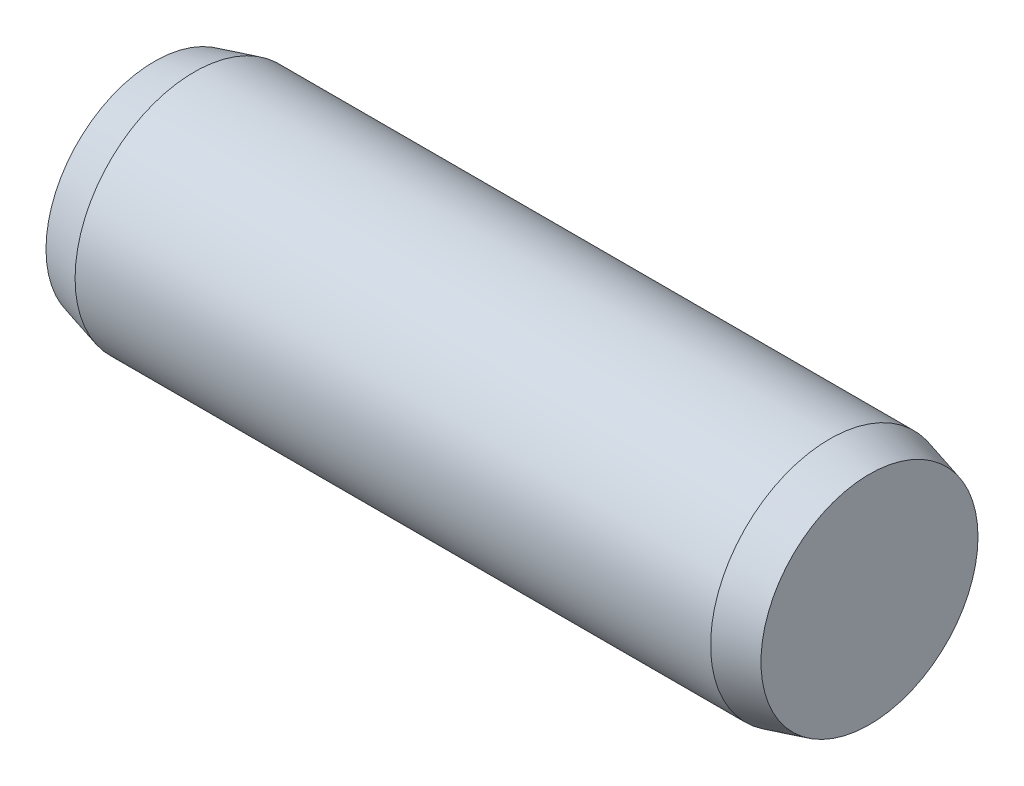
SolidWorks part; units mm, degrees
ref_plane "Front Plane" through (0, 0, 0) normal (0, 0, 1) x (1, 0, 0)
ref_plane "Top Plane" through (0, 0, 0) normal (0, 1, 0) x (1, 0, 0)
ref_plane "Right Plane" through (0, 0, 0) normal (1, 0, 0) x (0, 0, -1)
sketch "Sketch1" plane through (0, 0, 0) normal (0, 0, 1) x (1, 0, 0)
  line L0 (-4, 0) -> (4, 0) construction
  line L1 (4, 1.5) -> (4, -1.5) construction
  line L2 (-4, 1.5) -> (-4, -1.5) construction
  line L3 (4.5, 1.5) -> (4.5, -1.5) construction
  line L4 (-4.5, 1.5) -> (-4.5, -1.5) construction
  line L5 (-4, 0) -> (-4.5, 0) construction
  line L6 (4, 0) -> (4.5, 0) construction
  dimension "D1" = 0.5
  dimension "Dia" = 3
  dimension "Length" = 9
  dimension "C" = 0.5
sketch "Sketch2" plane through (0, 0, 0) normal (1, 0, 0) x (0, 0, -1)
  circle A0 centre (0, 0) radius 1.5
extrude "Extrude1" add sketch "Sketch2" against normal up to vertex (4 mm away) and the other way up to vertex (4 mm away) up to point (-4, 1.5, 0) other way up to point (4, 1.5, 0)
sketch "Sketch3" plane through (4, 0, 0) normal (1, 0, 0) x (0, 0, -1)
  circle A1 centre (0, 0) radius 1.5
  circle A2 centre (0, 0) radius 1.5
  dimension "D1" = 0
extrude "Extrude2" add sketch "Sketch3" along normal up to vertex (0.5 mm away) draft 15 up to point (4.5, 0, 0)
sketch "Sketch4" plane through (-4, 0, 0) normal (-1, 0, 0) x (0, 0, 1)
  circle A1 centre (0, 0) radius 1.5
  circle A2 centre (0, 0) radius 1.5
  dimension "D1" = 0
extrude "Extrude3" add sketch "Sketch4" along normal up to vertex (0.5 mm away) draft 15 up to point (-4.5, 0, 0)
equation "\"D1@Sketch1\" = \"C@Sketch1\""
